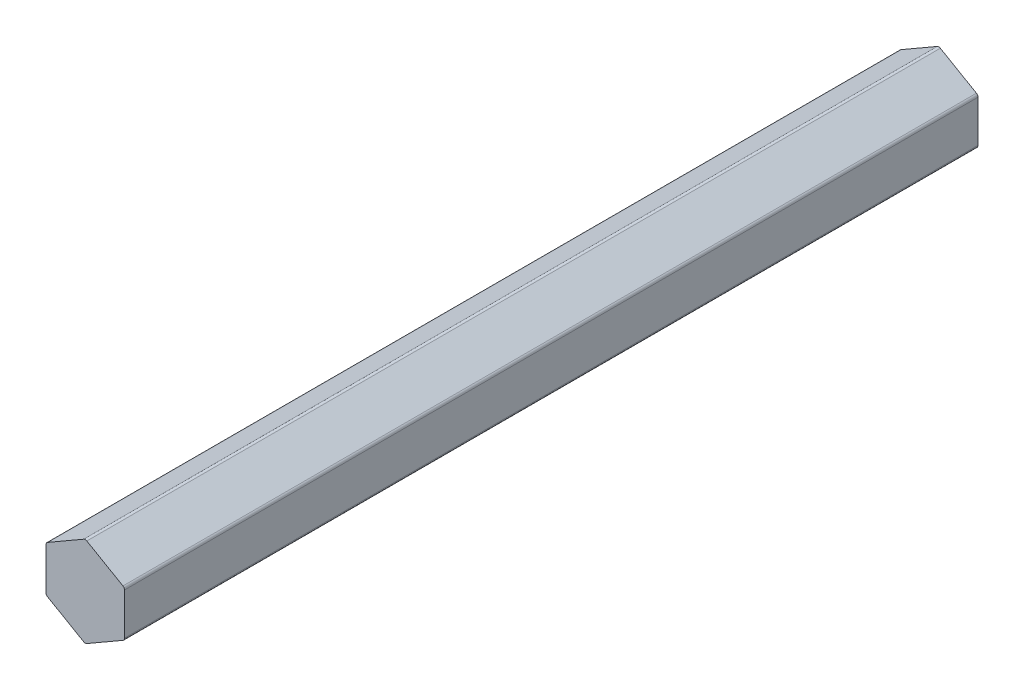
SolidWorks part; units mm, degrees
material "7075-T6 (SN)"
ref_plane "Front" through (0, 0, 0) normal (0, 0, 1) x (1, 0, 0)
ref_plane "Top" through (0, 0, 0) normal (0, 1, 0) x (1, 0, 0)
ref_plane "Right" through (0, 0, 0) normal (1, 0, 0) x (0, 0, -1)
sketch "Sketch1" plane through (0, 0, 0) normal (0, 0, 1) x (1, 0, 0)
  line L1 (0, 7.3323) -> (-6.35, 3.6662)
  line L2 (-6.35, 3.6662) -> (-6.35, -3.6662)
  line L3 (-6.35, -3.6662) -> (0, -7.3323)
  line L4 (0, -7.3323) -> (6.35, -3.6662)
  line L5 (6.35, -3.6662) -> (6.35, 3.6662)
  line L6 (6.35, 3.6662) -> (0, 7.3323)
  circle A0 centre (0, 0) radius 6.35 construction
extrude "Shaft Boss" add sketch "Sketch1" along normal up to surface (138.06 mm away)
fillet "Fillet1" radius 0.508 6 edges at (-6.35, -3.6662, 69.03) (0, -7.3323, 69.03) (6.35, -3.6662, 69.03) (-6.35, 3.6662, 69.03) (0, 7.3323, 69.03) (6.35, 3.6662, 69.03)
sketch "Sketch2" [suppressed] plane through (0, 0, 0) normal (0, 0, -1) x (-1, 0, 0)
  circle A0 centre (0, 0) radius 6.877
  circle A1 centre (0, 0) radius 9.417
extrude "Cut For Thunder Hex Round" [suppressed] cut sketch "Sketch2" against normal blind 914.4
sketch "Sketch3" [suppressed] plane through (0, 0, 0) normal (0, 0, -1) x (-1, 0, 0)
  circle A0 centre (0, 0) radius 2.5527
extrude "Center Hole Cut" [suppressed] cut sketch "Sketch3" against normal blind 914.4
equation "\"HS\"= 1 / 2"
equation "\"L\"= 36"
equation "\"D1@Sketch1\"=\"HS\""
equation "\"D1@Shaft Boss\" = \"L\""
equation "\"THOD\" = .4035"
equation "\"Fillet1\"     = \"unsuppressed\""
equation "\"Shaft Boss\"= \"unsuppressed\""
equation "\"D1@Sketch2\"=\"THOD\""
equation "\"D1@Cut For Thunder Hex Round\" = \"L\""
equation "\"Cut For Thunder Hex Round\"   = \"suppressed\""
equation "\"THID\" = .165"
equation "\"D1@Sketch3\"=\"THID\""
equation "\"D1@Center Hole Cut\" = \"L\""
equation "\"Center Hole Cut\"    = \"suppressed\""
